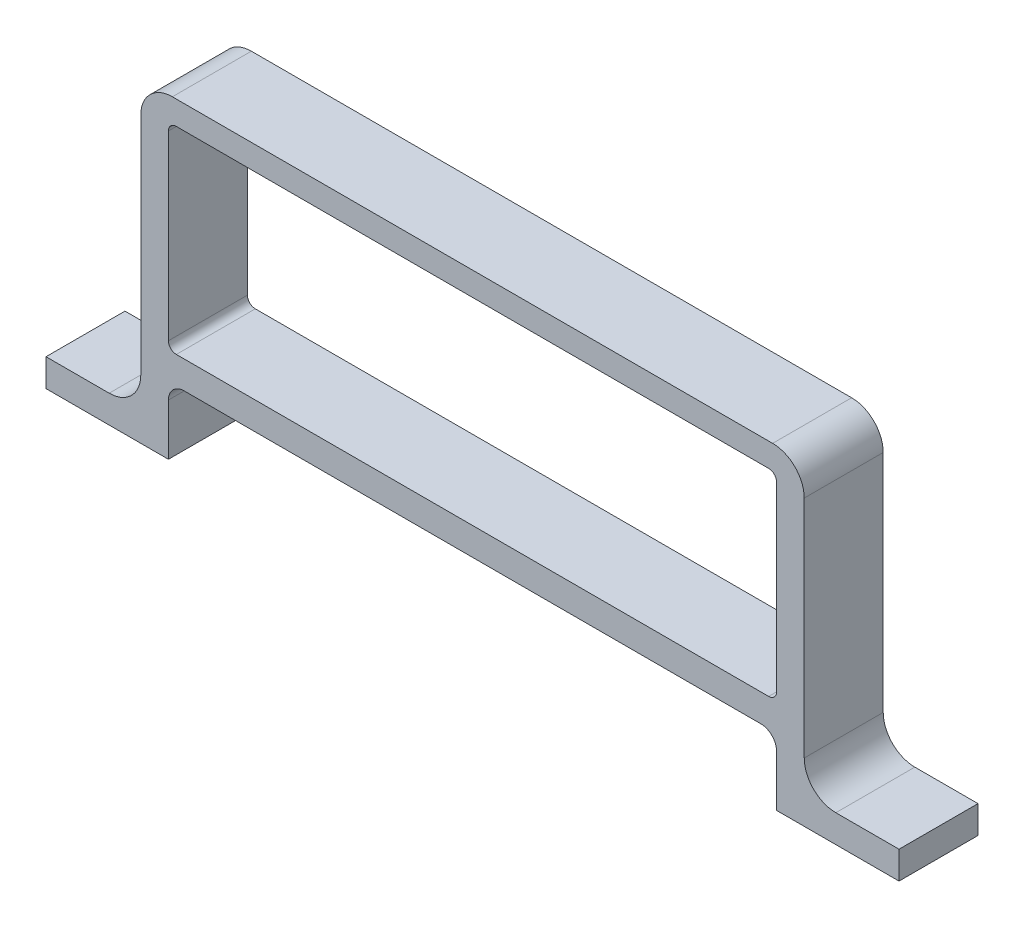
SolidWorks part; units mm, degrees
ref_plane "Alzado" through (0, 0, 0) normal (0, 0, 1) x (1, 0, 0)
ref_plane "Planta" through (0, 0, 0) normal (0, 1, 0) x (1, 0, 0)
ref_plane "Vista lateral" through (0, 0, 0) normal (1, 0, 0) x (0, 0, -1)
sketch "Croquis1" plane through (0, 0, 0) normal (0, 0, 1) x (1, 0, 0)
  line L2 (-39.6872, 1.2544) -> (-39.6872, 24.2544)
  line L7 (-43.1872, -3.2456) -> (-43.1872, 24.2544)
  line L8 (-38.6872, 25.2544) -> (-1.1872, 25.2544)
  line L10 (-43.1872, -4.2456) -> (-43.1872, -3.2456)
  line L13 (-39.6872, -5.2456) -> (-39.6872, -11.7456)
  line L15 (-39.6872, -11.7456) -> (-43.1872, -11.7456)
  line L17 (-43.1872, -11.7456) -> (-55.1872, -11.7456)
  line L21 (-43.1872, -11.7456) -> (-43.1872, -8.2456)
  line L22 (-47.1872, -8.2456) -> (-55.1872, -8.2456)
  line L23 (-55.1872, -11.7456) -> (-55.1872, -8.2456)
  line L24 (-1.1872, 25.2544) -> (-1.1872, 28.2544)
  line L25 (-1.1872, 28.2544) -> (-39.1872, 28.2544)
  line L26 (-37.6872, -3.2456) -> (-1.1872, -3.2456)
  line L27 (-1.1872, -3.2456) -> (-1.1872, 0.2544)
  line L28 (-1.1872, 0.2544) -> (-38.6872, 0.2544)
  arc A0 (-43.1872, 24.2544) -> (-39.1872, 28.2544) centre (-39.1872, 24.2544) cw
  arc A2 (-39.6872, 1.2544) -> (-38.6872, 0.2544) centre (-38.6872, 1.2544) ccw
  arc A3 (-39.6872, 24.2544) -> (-38.6872, 25.2544) centre (-38.6872, 24.2544) cw
  arc A5 (-39.6872, -5.2456) -> (-37.6872, -3.2456) centre (-37.6872, -5.2456) cw
  arc A10 (-43.1872, -4.2456) -> (-47.1872, -8.2456) centre (-47.1872, -4.2456) cw
  point P0 (-1.1872, 12.7544)
  dimension "D3" = 3.5
  dimension "D7" = 4
  dimension "D9" = 12.7544
  dimension "D5" = 2
  dimension "D6" = 37.5
  dimension "D4" = 4
  dimension "D17" = 1
  dimension "D2" = 3
  dimension "D8" = 37.5
  dimension "D10" = 3.5
  dimension "D11" = 6.5
  dimension "D12" = 8
  dimension "D13" = 12
  dimension "D14" = 3.5
  dimension "D15" = 36.5
  dimension "D16" = 23
extrude "Saliente-Extruir2" add sketch "Croquis1" along normal blind 10
mirror "Simetría2" about plane through (-1.1872, 0, 10) normal (-1, 0, 0) of "Saliente-Extruir2"
